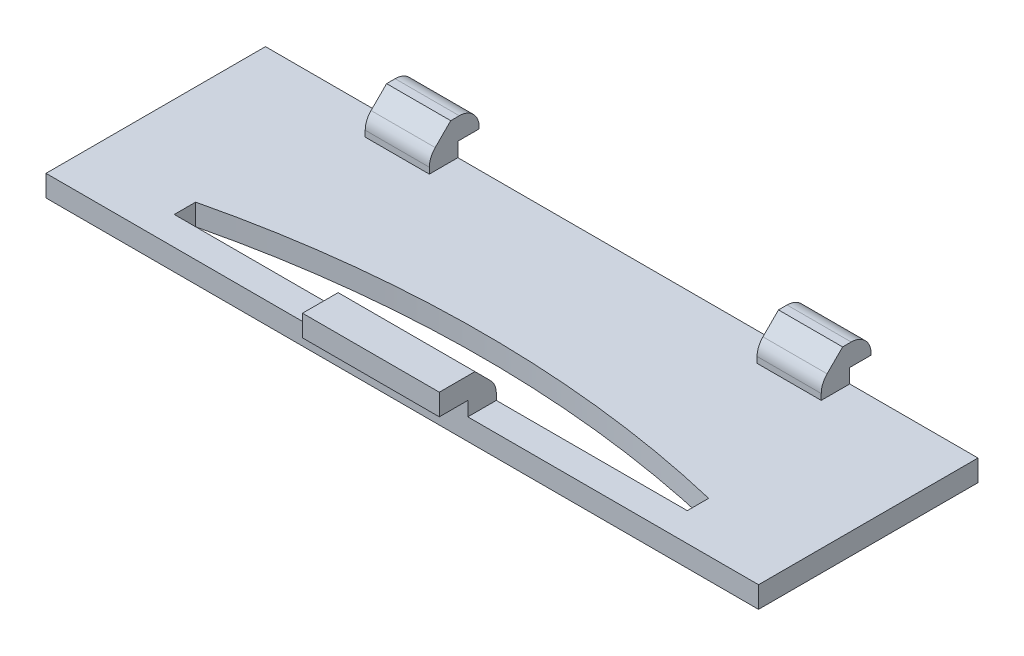
SolidWorks part; units mm, degrees
ref_plane "Front Plane" through (0, 0, 0) normal (0, 0, 1) x (1, 0, 0)
ref_plane "Top Plane" through (0, 0, 0) normal (0, 1, 0) x (1, 0, 0)
ref_plane "Right Plane" through (0, 0, 0) normal (1, 0, 0) x (0, 0, -1)
sketch "Sketch1" plane through (0, 0, 0) normal (0, 1, 0) x (1, 0, 0)
  line L1 (-36.2874, -2.6552) -> (-86.2874, -2.6552)
  line L2 (-36.2874, -2.6552) -> (-36.2874, 12.7448)
  line L3 (-36.2874, 12.7448) -> (-86.2874, 12.7448)
  line L4 (-86.2874, -2.6552) -> (-86.2874, 12.7448)
  line L5 (-79.2874, 0.8448) -> (-43.2874, 0.8448)
  line L6 (-79.2874, 0.8448) -> (-79.2874, -0.6552)
  line L7 (-79.2874, -0.6552) -> (-43.2874, -0.6552)
  line L8 (-43.2874, 0.8448) -> (-43.2874, -0.6552)
  point P8 (-43.2874, 0.0948)
  dimension "D1" = 15.4
  dimension "D2" = 50
  dimension "D3" = 7
  dimension "D4" = 7
  dimension "D5" = 2
  dimension "D6" = 1.5
extrude "Boss-Extrude1" add sketch "Sketch1" along normal blind 1.5
sketch "Sketch2" plane through (0, 1.5, 0) normal (0, 1, 0) x (1, 0, 0)
  line L0 (-79.2874, -0.6552) -> (-43.2874, -0.6552) construction
  line L1 (-66.2874, -0.6552) -> (-56.6874, -0.6552)
  line L2 (-66.2874, -0.6552) -> (-66.2874, -2.6552)
  line L3 (-66.2874, -2.6552) -> (-56.6874, -2.6552)
  line L4 (-56.6874, -0.6552) -> (-56.6874, -2.6552)
  line L5 (-86.2874, -2.6552) -> (-36.2874, -2.6552) construction
  line L6 (-36.2874, 12.7448) -> (-86.2874, 12.7448) construction
  line L7 (-77.2874, 12.7448) -> (-72.7874, 12.7448)
  line L8 (-77.2874, 12.7448) -> (-77.2874, 10.7448)
  line L9 (-77.2874, 10.7448) -> (-72.7874, 10.7448)
  line L10 (-72.7874, 12.7448) -> (-72.7874, 10.7448)
  line L12 (-49.7874, 12.7448) -> (-45.2874, 12.7448)
  line L13 (-49.7874, 12.7448) -> (-49.7874, 10.7448)
  line L14 (-49.7874, 10.7448) -> (-45.2874, 10.7448)
  line L15 (-45.2874, 12.7448) -> (-45.2874, 10.7448)
  dimension "D1" = 20
  dimension "D2" = 20.4
  dimension "D3" = 9
  dimension "D4" = 9
  dimension "D5" = 4.5
  dimension "D6" = 4.5
  dimension "D7" = 2
extrude "Boss-Extrude2" add sketch "Sketch2" along normal blind 2.5
chamfer "Chamfer3" distance 1.5 angle 45 1 edges at (-75.0374, 4, -10.7448)
chamfer "Chamfer4" distance 1.5 angle 45 2 edges at (-61.4874, 4, 0.6552) (-47.5374, 4, -10.7448)
fillet "Fillet3" radius 1.4 2 edges at (-47.5374, 2.5, -10.7448) (-75.0374, 2.5, -10.7448)
sketch "Sketch5" plane through (0, 0, 2.6552) normal (0, 0, 1) x (1, 0, 0)
  line L1 (-66.2874, 4) -> (-56.6874, 4)
  line L2 (-66.2874, 4) -> (-66.2874, 1.5)
  line L3 (-66.2874, 1.5) -> (-56.6874, 1.5) construction
  line L4 (-56.6874, 4) -> (-56.6874, 1.5)
  line L5 (-56.6874, 4) -> (-66.2874, 4)
  line L6 (-56.6874, 4) -> (-56.6874, 1.5)
  line L7 (-56.6874, 1.5) -> (-66.2874, 1.5)
  line L8 (-66.2874, 4) -> (-66.2874, 1.5)
  line L9 (-56.6874, 4) -> (-66.2874, 4)
  line L10 (-56.6874, 4) -> (-56.6874, 2.5)
  line L11 (-56.6874, 2.5) -> (-66.2874, 2.5)
  line L12 (-66.2874, 4) -> (-66.2874, 2.5)
  line M9 (-56.6874, 4) -> (-66.2874, 4)
  line M10 (-66.2874, 4) -> (-66.2874, 1.5)
  dimension "D1" = 1.5
extrude "Boss-Extrude4" add sketch "Sketch5" along normal blind 2 contours L11 L6 M9 M10
fillet "Fillet4" radius 1.4 1 edges at (-61.4874, 2.5, 0.6552)
sketch "Sketch6" plane through (0, 0, -12.7448) normal (0, 0, -1) x (-1, 0, 0)
  line L0 (49.7874, 4) -> (49.7874, 1.5) construction
  line L1 (45.2874, 4) -> (49.7874, 4)
  line L2 (45.2874, 4) -> (45.2874, 2.5)
  line L3 (45.2874, 2.5) -> (49.7874, 2.5)
  line L4 (49.7874, 4) -> (49.7874, 2.5)
  line L5 (77.2874, 4) -> (77.2874, 1.5) construction
  line L6 (72.7874, 4) -> (77.2874, 4)
  line L7 (72.7874, 4) -> (72.7874, 2.5)
  line L8 (72.7874, 2.5) -> (77.2874, 2.5)
  line L9 (77.2874, 4) -> (77.2874, 2.5)
extrude "Boss-Extrude5" add sketch "Sketch6" along normal blind 1.5
fillet "Fillet5" radius 1.4 2 edges at (-75.0374, 4, -14.2448) (-47.5374, 4, -14.2448)
sketch "Sketch7" plane through (0, 1.5, 0) normal (0, 1, 0) x (1, 0, 0)
  line L0 (-79.2874, 0.8448) -> (-43.2874, 0.8448)
  arc A0 (-79.2874, 0.8448) -> (-43.2874, 0.8448) centre (-61.2874, -74.3895) cw
extrude "Cut-Extrude5" cut sketch "Sketch7" along normal through all and the other way through all
